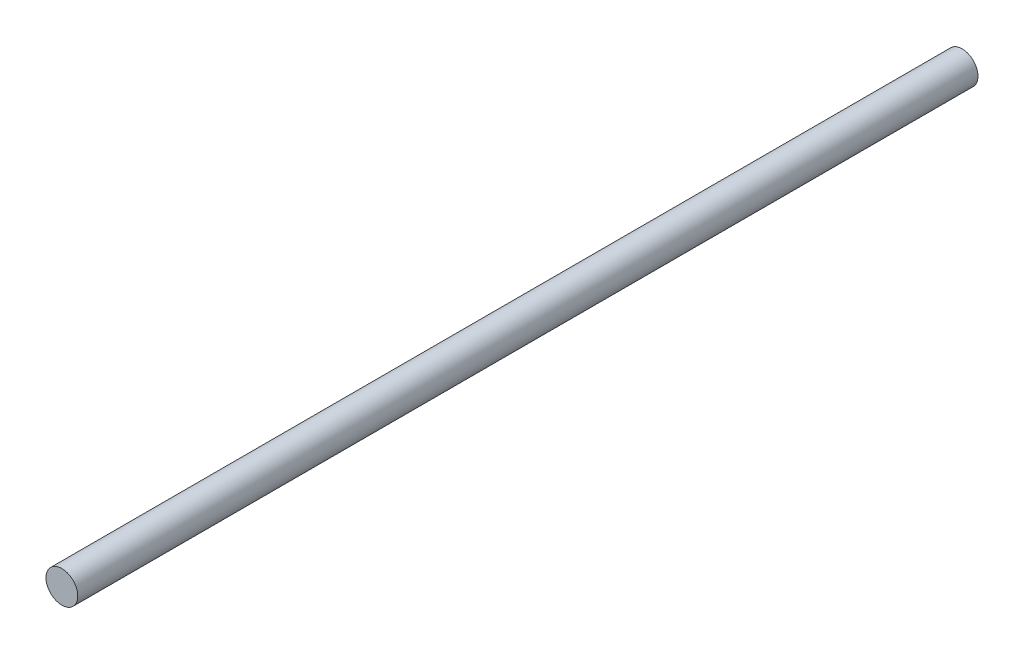
SolidWorks part; units mm, degrees
ref_plane "前视基准面" through (0, 0, 0) normal (0, 0, 1) x (1, 0, 0)
ref_plane "上视基准面" through (0, 0, 0) normal (0, 1, 0) x (1, 0, 0)
ref_plane "右视基准面" through (0, 0, 0) normal (1, 0, 0) x (0, 0, -1)
sketch "草图1" plane through (0, 0, 0) normal (0, 0, 1) x (1, 0, 0)
  circle A0 centre (0, 0) radius 3
  dimension "D1" = 6
extrude "凸台-拉伸1" add sketch "草图1" along normal blind 170
